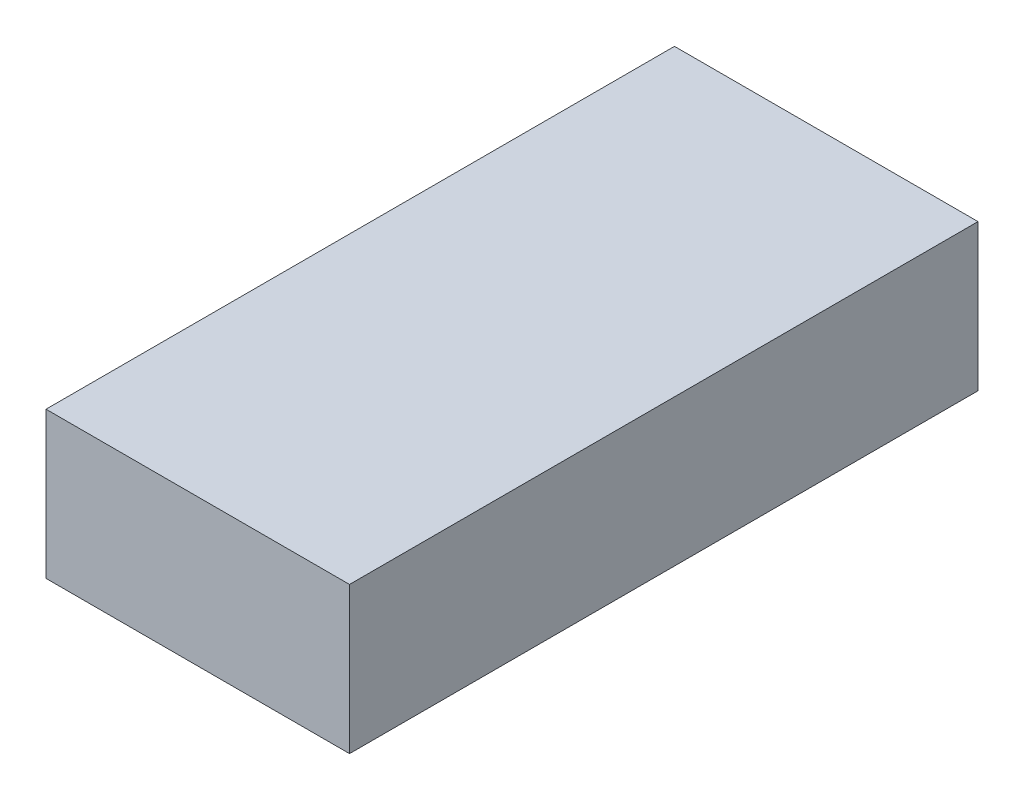
SolidWorks part; units mm, degrees
ref_plane "Front Plane" through (0, 0, 0) normal (0, 0, 1) x (1, 0, 0)
ref_plane "Top Plane" through (0, 0, 0) normal (0, 1, 0) x (1, 0, 0)
ref_plane "Right Plane" through (0, 0, 0) normal (1, 0, 0) x (0, 0, -1)
sketch "Sketch2" plane through (0, 0, 0) normal (0, 0, 1) x (1, 0, 0)
  line L1 (0, 0) -> (52.4, 0)
  line L2 (0, 0) -> (0, 25.3)
  line L3 (0, 25.3) -> (52.4, 25.3)
  line L4 (52.4, 0) -> (52.4, 25.3)
  dimension "D1" = 25.3
  dimension "D2" = 52.4
extrude "Boss-Extrude1" add sketch "Sketch2" along normal blind 108.5
